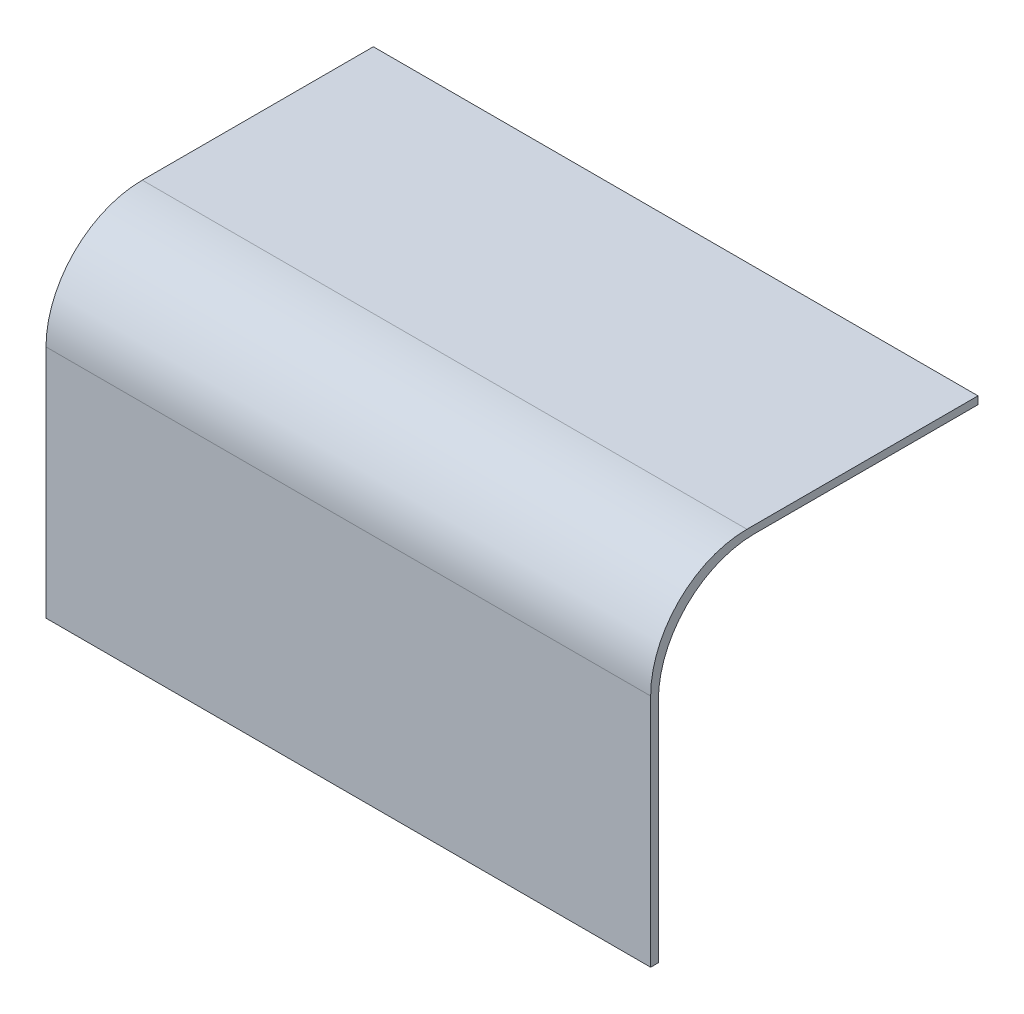
SolidWorks part; units mm, degrees
ref_plane "Alzado" through (0, 0, 0) normal (0, 0, 1) x (1, 0, 0)
ref_plane "Planta" through (0, 0, 0) normal (0, 1, 0) x (1, 0, 0)
ref_plane "Vista lateral" through (0, 0, 0) normal (1, 0, 0) x (0, 0, -1)
sketch "Croquis2" plane through (0, 0, 0) normal (1, 0, 0) x (0, 0, -1)
  line L0 (-38.5721, -20.4089) -> (-38.5721, 101.5911)
  line L1 (11.4279, 151.5911) -> (131.4279, 151.5911)
  line L2 (131.4279, 151.5911) -> (131.4279, 147.5911)
  line L3 (131.4279, 147.5911) -> (15.4279, 147.5911)
  line L4 (-34.5721, 97.5911) -> (-34.5721, -20.4089)
  line L5 (-34.5721, -20.4089) -> (-38.5721, -20.4089)
  arc A0 (15.4279, 147.5911) -> (-34.5721, 97.5911) centre (15.4279, 97.5911) ccw
  arc A1 (-38.5721, 101.5911) -> (11.4279, 151.5911) centre (11.4279, 101.5911) cw
  point P10 (-38.5721, 151.5911)
  dimension "D2" = 50
  dimension "D1" = 172
  dimension "D3" = 170
  dimension "D4" = 4
extrude "Saliente-Extruir1" add sketch "Croquis2" against normal blind 314
sketch "Croquis3" plane through (0, 0, 34.5721) normal (0, 0, -1) x (-1, 0, 0)
  line L0 (2, 97.5911) -> (2, -18.4089)
  line L1 (2, -18.4089) -> (312, -18.4089)
  line L2 (312, -18.4089) -> (312, 97.5911)
  line L3 (312, 97.5911) -> (308, 97.5911)
  line L4 (308, 97.5911) -> (308, -14.4089)
  line L5 (308, -14.4089) -> (6, -14.4089)
  line L6 (6, -14.4089) -> (6, 97.5911)
  line L7 (6, 97.5911) -> (2, 97.5911)
  line L8 (0, -20.4089) -> (0, 97.5911) construction
  point P11 (2, 97.5911)
  dimension "D1" = 310
  dimension "D2" = 4
  dimension "D3" = 2
  dimension "D4" = 2
  dimension "D5" = 4
extrude "Cortar-Extruir1" cut sketch "Croquis3" against normal blind 2
equation "\"venesta\"= 4'grosor de la venesta"
equation "\"policarbonato\"= 4'grosor del policarbonato"
equation "\"carton_trupan\"= 3'grosor del carton trupan caso laser"
equation "\"ancho_tot\"= 310'ancho tot sin llantas"
equation "\"largo_tot\"= 400'largo tot sin camera"
equation "\"alto_estimado\"= 300'alto estimado sin lidar"
equation "\"altoparaqpaselabotella\"= 75'alto estimado para que encaje la botella"
equation "\"alturaruedaloca\"= 22"
equation "\"anchoruedaloca\"= 35"
equation "\"anchopiso1motorybaterias\"= 150"
equation "\"dist-pisorampa\"= 5"
equation "\"anchoultimopiso\"= 170"
equation "\"paredtrasera\"= 100"
equation "\"agarradorcanasta\"= 275'recolector"
equation "\"alturapiso1y2\"= 80"
equation "\"alturapiso2y3\"= 80"
equation "\"D1@Croquis2\"=\"venesta\"+\"alturapiso1y2\"+\"venesta\"+\"alturapiso2y3\"+\"venesta\""
equation "\"D3@Croquis2\" = \"ancho_techo\""
equation "\"D4@Croquis2\" = \"ancho_impresion\""
equation "\"D1@Saliente-Extruir1\"=\"ancho_tot\"+\"ancho_impresion\""
equation "\"ancho_techo\"= 170"
equation "\"ancho_impresion\"= 4"
equation "\"D1@Croquis3\"=\"ancho_tot\""
equation "\"D2@Croquis3\"=\"policarbonato\""
equation "\"D5@Croquis3\"=\"venesta\""
